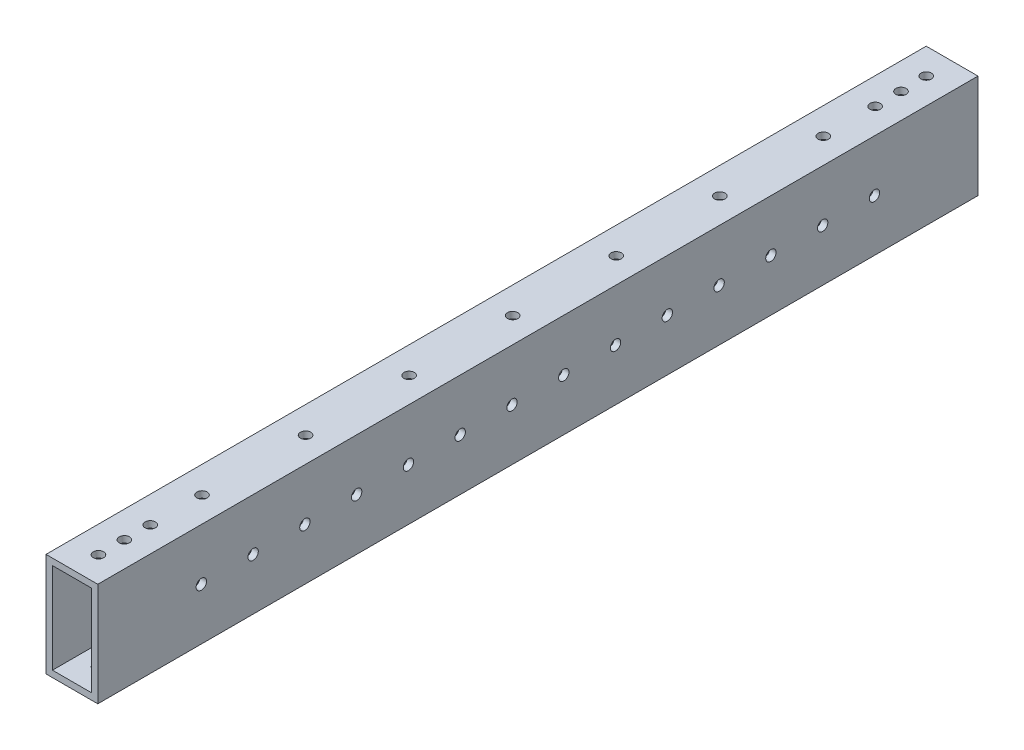
SolidWorks part; units mm, degrees
ref_plane "Front Plane" through (0, 0, 0) normal (0, 0, 1) x (1, 0, 0)
ref_plane "Top Plane" through (0, 0, 0) normal (0, 1, 0) x (1, 0, 0)
ref_plane "Right Plane" through (0, 0, 0) normal (1, 0, 0) x (0, 0, -1)
sketch "Sketch1" plane through (0, 0, 0) normal (0, 0, 1) x (1, 0, 0)
  line L1 (0, 0) -> (25.4, 0)
  line L2 (0, 0) -> (0, 50.8)
  line L3 (0, 50.8) -> (25.4, 50.8)
  line L4 (25.4, 0) -> (25.4, 50.8)
  line L5 (3.175, 3.175) -> (22.225, 3.175)
  line L6 (3.175, 3.175) -> (3.175, 47.625)
  line L7 (3.175, 47.625) -> (22.225, 47.625)
  line L8 (22.225, 3.175) -> (22.225, 47.625)
  dimension "D1" = 25.4
  dimension "D2" = 50.8
  dimension "D3" = 3.175
  dimension "D4" = 3.175
  dimension "D5" = 3.175
  dimension "D6" = 3.175
extrude "Boss-Extrude1" add sketch "Sketch1" along normal blind 431.8
sketch "Sketch2" plane through (0, 50.8, 0) normal (0, 1, 0) x (1, 0, 0)
  line L0 (25.4, -431.8) -> (25.4, 0) construction
  line L1 (25.4, 0) -> (0, 0) construction
  line L2 (25.4, -431.8) -> (0, -431.8) construction
  circle A0 centre (12.7, -12.7) radius 2.54
  circle A1 centre (13.0297, -25.4) radius 2.54
  circle A2 centre (13.0297, -38.1) radius 2.54
  circle A3 centre (13.0297, -406.4) radius 2.54
  circle A4 centre (13.0297, -419.1) radius 2.54
  circle A5 centre (13.0297, -393.7) radius 2.54
  circle A6 centre (13.0297, -368.3) radius 2.54
  circle A7 centre (13.0297, -317.5) radius 2.54
  circle A8 centre (13.0297, -266.7) radius 2.54
  circle A9 centre (13.0297, -215.9) radius 2.54
  circle A10 centre (13.0297, -165.1) radius 2.54
  circle A11 centre (13.0297, -114.3) radius 2.54
  circle A12 centre (13.0297, -63.5) radius 2.54
  dimension "D1" = 5.08
  dimension "D9" = 5.08
  dimension "D2" = 12.7
  dimension "D3" = 12.7
  dimension "D4" = 12.7
  dimension "D5" = 12.7
  dimension "D6" = 12.7
  dimension "D7" = 12.7
  dimension "D8" = 12.7
  dimension "D10" = 63.5
  dimension "D11" = 7
extrude "Cut-Extrude1" cut sketch "Sketch2" against normal through all
sketch "Sketch3" plane through (25.4, 0, 0) normal (1, 0, 0) x (0, 0, -1)
  line L0 (-431.8, 0) -> (0, 0) construction
  line L1 (-431.8, 0) -> (-431.8, 50.8) construction
  circle A0 centre (-381, 25.4) radius 2.54
  circle A22 centre (-355.6, 25.4) radius 2.54
  circle A23 centre (-330.2, 25.4) radius 2.54
  circle A24 centre (-304.8, 25.4) radius 2.54
  circle A25 centre (-279.4, 25.4) radius 2.54
  circle A26 centre (-254, 25.4) radius 2.54
  circle A27 centre (-228.6, 25.4) radius 2.54
  circle A28 centre (-203.2, 25.4) radius 2.54
  circle A29 centre (-177.8, 25.4) radius 2.54
  circle A30 centre (-152.4, 25.4) radius 2.54
  circle A31 centre (-127, 25.4) radius 2.54
  circle A32 centre (-101.6, 25.4) radius 2.54
  circle A33 centre (-76.2, 25.4) radius 2.54
  circle A34 centre (-50.8, 25.4) radius 2.54
  dimension "D1" = 5.08
  dimension "D2" = 25.4
  dimension "1.5" = 50.8
  dimension "D4" = 14
extrude "Cut-Extrude2" cut sketch "Sketch3" against normal through all
